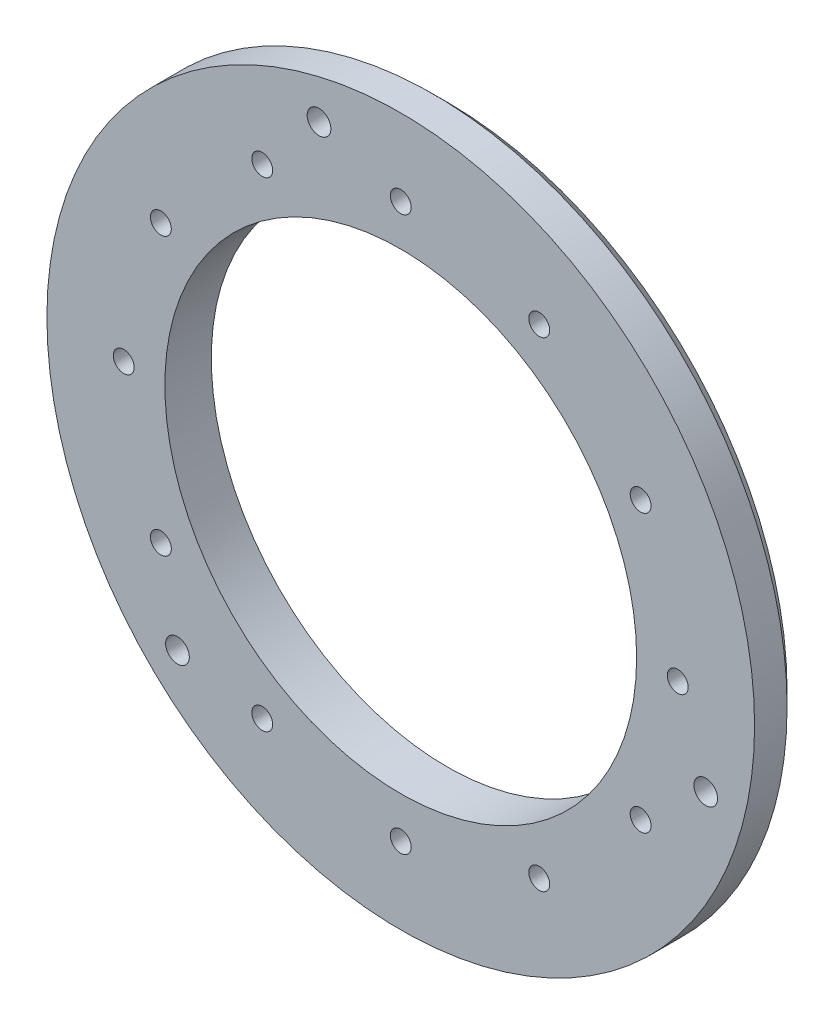
SolidWorks part; units mm, degrees
material "6061-T6 (SS)"
ref_plane "Plan de face" through (0, 0, 0) normal (0, 0, 1) x (1, 0, 0)
ref_plane "Plan de dessus" through (0, 0, 0) normal (0, 1, 0) x (1, 0, 0)
ref_plane "Plan de droite" through (0, 0, 0) normal (1, 0, 0) x (0, 0, -1)
sketch "Esquisse2" plane through (0, 0, 0) normal (0, 0, 1) x (1, 0, 0)
  circle A0 centre (0, 0) radius 76.2
  circle A1 centre (0, 0) radius 50.8
  dimension "D1" = 101.6
  dimension "D2" = 152.4
extrude "Boss.-Extru.1" add sketch "Esquisse2" along normal blind 10
chamfer "Chanfrein1" distance 3 angle 45 1 edges at (76.2, 0, 0)
hole_wizard "Dégagement #81" positions "Esquisse3" profile "Esquisse4" hole size "#8" standard "Ansi Inch" end condition through all
sketch "Esquisse3" plane through (0, 0, 0) normal (0, 0, -1) x (-1, 0, 0)
  point P0 (0, 59.65)
  point P3 (51.6584, 29.825)
  point P6 (29.825, 51.6584)
  point P9 (59.65, 0)
  point P12 (51.6584, -29.825)
  point P15 (29.825, -51.6584)
  point P18 (0, -59.65)
  point P21 (-29.825, -51.6584)
  point P24 (-51.6584, -29.825)
  point P27 (-59.65, 0)
  point P30 (-51.6584, 29.825)
  point P33 (-29.825, 51.6584)
sketch "Esquisse4" plane through (0, 59.65, 0) normal (1, 0, 0) x (0, 1, 0)
  line L0 (0, 0) -> (0, 10)
  line L1 (0, 10) -> (2.2479, 10)
  line L2 (2.2479, 10) -> (2.2479, 0)
  line L5 (2.2479, 0) -> (0, 0)
  line L11 (0, -6.35) -> (0, 107.95) construction
  dimension "Diamètre du perçage jusqu'au prochain" = 4.4958
  dimension "Profondeur du perçage jusqu'au prochain" = 10
hole_wizard "Fraisage pour vis à tête fraisée bombée #101" positions "Esquisse5" profile "Esquisse6" countersink size "#10" standard "Ansi Inch" end condition through all
sketch "Esquisse5" plane through (0, 0, 0) normal (0, 0, -1) x (-1, 0, 0)
  line L0 (17.5997, 65.683) -> (48.0833, -48.0833) construction
  line L1 (48.0833, -48.0833) -> (-65.683, -17.5997) construction
  line L2 (-65.683, -17.5997) -> (17.5997, 65.683) construction
  line L3 (17.5997, 65.683) -> (0, 0) construction
  line L4 (0, 0) -> (-65.683, -17.5997) construction
  line L6 (0, 0) -> (48.0833, -48.0833) construction
  line L8 (29.825, 51.6584) -> (51.6584, -29.825) construction
  circle A1 centre (29.825, 51.6584) radius 2.2479 construction
  circle A2 centre (51.6584, -29.825) radius 2.2479 construction
  circle A3 centre (29.825, 51.6584) radius 2.2479 construction
  circle A4 centre (51.6584, -29.825) radius 2.2479 construction
  point P0 (48.0833, -48.0833)
  point P2 (-65.683, -17.5997)
  point P4 (17.5997, 65.683)
  dimension "D1" = 68
sketch "Esquisse6" plane through (-48.0833, -48.0833, 0) normal (1, 0, 0) x (0, 1, 0)
  line L0 (0, 0) -> (0, 10)
  line L1 (0, 10) -> (2.5527, 10)
  line L2 (2.5527, 10) -> (2.5527, 2.6882)
  line L3 (2.5527, 2.6882) -> (4.8895, 0)
  line L5 (4.8895, 0) -> (0, 0)
  line L6 (-2.5527, 2.6882) -> (-4.8895, 0) construction
  line L11 (0, -6.35) -> (0, 107.95) construction
  dimension "Diamètre du perçage jusqu'au prochain" = 5.1054
  dimension "Profondeur du perçage jusqu'au prochain" = 10
  dimension "Diamètre du fraisage entrant" = 9.779
  dimension "Angle du fraisage entrant" = 82
